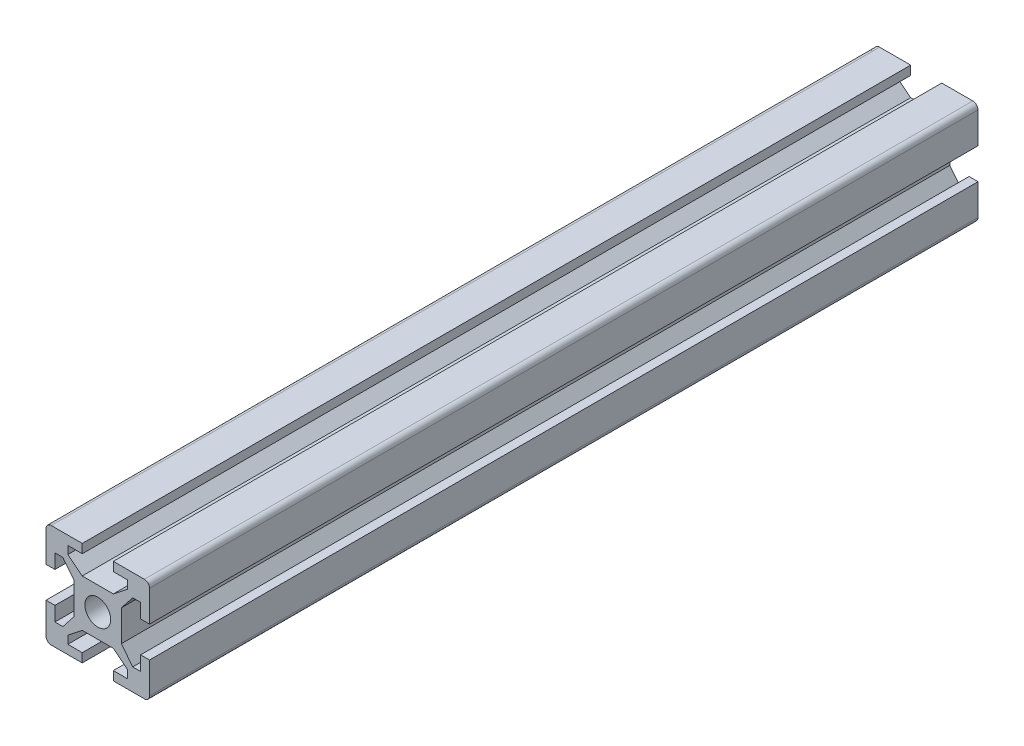
SolidWorks part; units mm, degrees
ref_plane "Front Plane" through (0, 0, 0) normal (0, 0, 1) x (1, 0, 0)
ref_plane "Top Plane" through (0, 0, 0) normal (0, 1, 0) x (1, 0, 0)
ref_plane "Right Plane" through (0, 0, 0) normal (1, 0, 0) x (0, 0, -1)
sketch "Sketch1" plane through (0, 0, 0) normal (0, 0, 1) x (1, 0, 0)
  line L18 (0, 0) -> (0, 20.5117) construction
  line L39 (-10, 10) -> (-3, 10)
  line L41 (10, 10) -> (3, 10)
  line L43 (-10, 10) -> (-10, 3)
  line L45 (-10, -10) -> (-10, -3)
  line L47 (-10, -10) -> (-3, -10)
  line L49 (3, -10) -> (10, -10)
  line L51 (10, -10) -> (10, -3)
  line L53 (10, 3) -> (10, 10)
  line L55 (-3, 10) -> (-3, 8.2726)
  line L56 (-3, 8.2726) -> (-5.7838, 8.2726)
  line L57 (-5.7838, 8.2726) -> (-5.7838, 6.748)
  line L58 (-5.7838, 6.748) -> (-3, 4.5508)
  line L59 (-3, 4.5508) -> (3, 4.5508)
  line L60 (3, 10) -> (3, 8.2726)
  line L61 (3, 8.2726) -> (5.7838, 8.2726)
  line L62 (5.7838, 8.2726) -> (5.7838, 6.748)
  line L63 (5.7838, 6.748) -> (3, 4.5508)
  line L64 (10, 3) -> (8.2726, 3)
  line L65 (8.2726, 3) -> (8.2726, 5.7838)
  line L66 (8.2726, 5.7838) -> (6.748, 5.7838)
  line L67 (10, -3) -> (8.2726, -3)
  line L68 (8.2726, -3) -> (8.2726, -5.7838)
  line L69 (8.2726, -5.7838) -> (6.748, -5.7838)
  line L70 (4.55, -2.9994) -> (4.55, 3.0006)
  line L71 (4.55, -2.9994) -> (6.748, -5.7838)
  line L72 (4.55, 3.0006) -> (6.748, 5.7838)
  line L73 (3, -10) -> (3, -8.2726)
  line L74 (3, -8.2726) -> (5.7838, -8.2726)
  line L75 (5.7838, -8.2726) -> (5.7838, -6.748)
  line L76 (-3, -10) -> (-3, -8.2726)
  line L77 (-3, -8.2726) -> (-5.7838, -8.2726)
  line L78 (-5.7838, -8.2726) -> (-5.7838, -6.748)
  line L79 (2.9994, -4.55) -> (-3.0006, -4.55)
  line L80 (5.7838, -6.748) -> (2.9994, -4.55)
  line L81 (-5.7838, -6.748) -> (-3.0006, -4.55)
  line L82 (-10, -3) -> (-8.2726, -3)
  line L83 (-8.2726, -3) -> (-8.2726, -5.7838)
  line L84 (-8.2726, -5.7838) -> (-6.748, -5.7838)
  line L85 (-10, 3) -> (-8.2726, 3)
  line L86 (-8.2726, 3) -> (-8.2726, 5.7838)
  line L87 (-8.2726, 5.7838) -> (-6.748, 5.7838)
  line L88 (-4.55, -3.0006) -> (-4.55, 2.9994)
  line L89 (-6.748, -5.7838) -> (-4.55, -3.0006)
  line L90 (-4.55, 2.9994) -> (-6.748, 5.7838)
  dimension "D9" = 7
  dimension "D17" = 2.7838
  dimension "D1" = 20
  dimension "D2" = 20
  dimension "D3" = 10
  dimension "D4" = 10
  dimension "D5" = 7
  dimension "D6" = 7
  dimension "D7" = 7
  dimension "D8" = 7
  dimension "D10" = 7
  dimension "D11" = 7
  dimension "D12" = 7
  dimension "D13" = 6
  dimension "D14" = 3
  dimension "D15" = 3.5464
  dimension "D16" = 1.5246
  dimension "D18" = 1.7274
  dimension "D19" = 4.55
  dimension "D20" = 4.55
  dimension "D21" = 4.55
  dimension "D22" = 10
  dimension "D23" = 10
  dimension "D24" = 10
  dimension "D25" = 10
  dimension "D26" = 10
  dimension "D27" = 10
  dimension "D28" = 6
  dimension "D29" = 6
  dimension "D30" = 6
  dimension "D31" = 6
extrude "Boss-Extrude1" add sketch "Sketch1" along normal mid plane 160
sketch "Sketch2" plane through (0, 0, 80) normal (0, 0, 1) x (1, 0, 0)
  circle A0 centre (0, 0) radius 2.5
  dimension "D1" = 5
extrude "Cut-Extrude1" cut sketch "Sketch2" against normal through all both and the other way through all
fillet "Fillet1" radius 1 4 edges at (-10, -10, 0) (10, -10, 0) (10, 10, 0) (-10, 10, 0)
